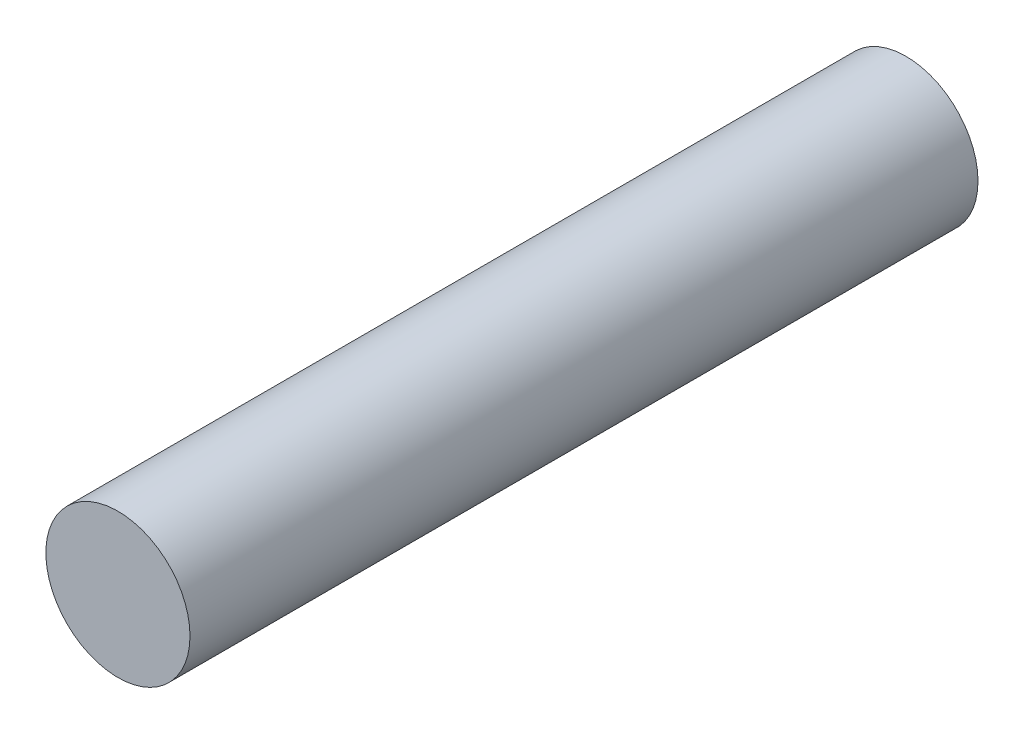
SolidWorks part; units mm, degrees
ref_plane "Alzado" through (0, 0, 0) normal (0, 0, 1) x (1, 0, 0)
ref_plane "Planta" through (0, 0, 0) normal (0, 1, 0) x (1, 0, 0)
ref_plane "Vista lateral" through (0, 0, 0) normal (1, 0, 0) x (0, 0, -1)
sketch "Croquis1" plane through (0, 0, 0) normal (0, 0, 1) x (1, 0, 0)
  circle A0 centre (0, 0) radius 7.5
  dimension "D1" = 15
extrude "Saliente-Extruir1" add sketch "Croquis1" along normal blind 82
